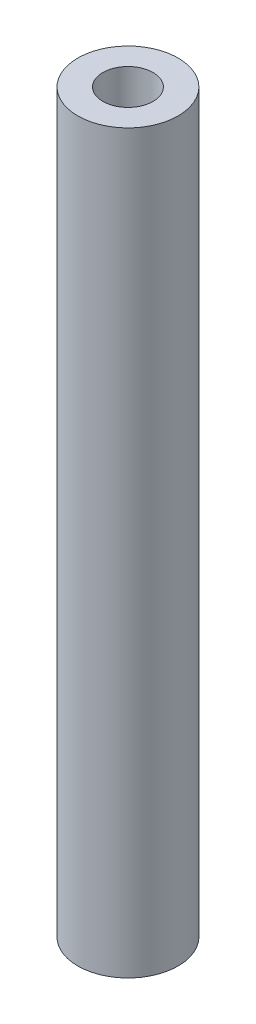
SolidWorks part; units mm, degrees
ref_plane "Front Plane" through (0, 0, 0) normal (0, 0, 1) x (1, 0, 0)
ref_plane "Top Plane" through (0, 0, 0) normal (0, 1, 0) x (1, 0, 0)
ref_plane "Right Plane" through (0, 0, 0) normal (1, 0, 0) x (0, 0, -1)
sketch "Sketch1" plane through (0, 0, 0) normal (0, 1, 0) x (1, 0, 0)
  circle A0 centre (0, 0) radius 5.842
  circle A1 centre (0, 0) radius 2.921
extrude "Boss-Extrude1" add sketch "Sketch1" along normal blind 85.725 contours A1 | A0
